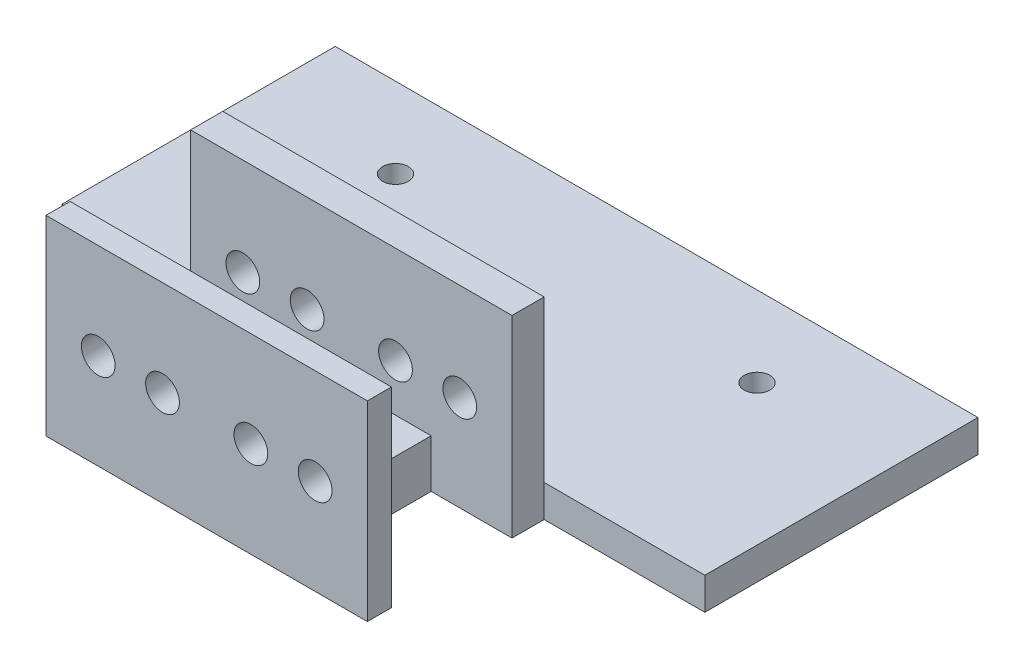
SolidWorks part; units mm, degrees
ref_plane "前视基准面" through (0, 0, 0) normal (0, 0, 1) x (1, 0, 0)
ref_plane "上视基准面" through (0, 0, 0) normal (0, 1, 0) x (1, 0, 0)
ref_plane "右视基准面" through (0, 0, 0) normal (1, 0, 0) x (0, 0, -1)
other "Configuration Table"
sketch "草图1" plane through (0, 0, 0) normal (0, 1, 0) x (1, 0, 0)
  line L1 (-40, 17) -> (40, 17)
  line L2 (-40, 17) -> (-40, -17)
  line L3 (-40, -17) -> (40, -17)
  line L4 (40, 17) -> (40, -17)
  line L5 (-40, 17) -> (40, -17) construction
  line L6 (-40, -17) -> (40, 17) construction
  point P0 (0, 0)
  dimension "D1" = 80
  dimension "D2" = 34
extrude "凸台-拉伸1" add sketch "草图1" along normal blind 4
sketch "草图2" plane through (0, 4, 0) normal (0, 1, 0) x (1, 0, 0)
  line L0 (-40, 7) -> (40, 7) construction
  line L1 (-40, 17) -> (-40, -17) construction
  line L2 (40, -17) -> (40, 17) construction
  line L4 (40, 17) -> (-40, 17) construction
  circle A0 centre (-22.5, 7) radius 1.6
  circle A1 centre (22.5, 7) radius 1.6
  point P8 (0, 7)
  point P9 (22.5, 7)
  point P10 (-22.5, 7)
  dimension "D1" = 10
  dimension "D2" = 22.5
  dimension "D3" = 22.5
extrude "切除-拉伸1" cut sketch "草图2" against normal up to next
sketch "草图3" plane through (0, 0, 17) normal (0, 0, 1) x (1, 0, 0)
  line L0 (-40, 0) -> (40, 0) construction
  line L1 (-20, 0) -> (20, 0)
  line L2 (-20, 0) -> (-20, 24)
  line L3 (20, 0) -> (20, 24)
  line L4 (-20, 24) -> (20, 24)
  point P0 (-20, 0)
  point P1 (20, 0)
  dimension "D1" = 20
  dimension "D2" = 20
extrude "凸台-拉伸2" add sketch "草图3" along normal blind 4
sketch "草图4" plane through (0, 0, 21) normal (0, 0, 1) x (1, 0, 0)
  line L0 (-20, 12) -> (20, 12) construction
  line L1 (-20, 24) -> (-20, 0) construction
  line L2 (20, 0) -> (20, 24) construction
  line L3 (-20, 3) -> (19.876, 3) construction
  line L4 (-20, 0) -> (20, 0) construction
  line L5 (-10.062, 6) -> (9.938, 6)
  line L6 (-10.062, 6) -> (-10.062, 0)
  line L7 (-10.062, 0) -> (9.938, 0)
  line L8 (9.938, 6) -> (9.938, 0)
  line L9 (-10.062, 6) -> (9.938, 0) construction
  line L10 (-10.062, 0) -> (9.938, 6) construction
  point P8 (-0.062, 3)
  dimension "D1" = 9
  dimension "D2" = 20
extrude "凸台-拉伸3" add sketch "草图4" along normal blind 15
sketch "草图5" plane through (0, 0, 36) normal (0, 0, 1) x (1, 0, 0)
  line L0 (-20, 0) -> (20, 0)
  line L1 (-20, 0) -> (-20, 23.7906)
  line L2 (20, 0) -> (20, 23.7906)
  line L3 (-20, 23.7906) -> (20, 23.7906)
extrude "凸台-拉伸4" add sketch "草图5" along normal blind 3
sketch "草图6" plane through (0, 0, 39) normal (0, 0, 1) x (1, 0, 0)
  line L0 (-20, 11.8953) -> (20, 11.8953) construction
  line L1 (-20, 23.7906) -> (-20, 0) construction
  line L2 (20, 0) -> (20, 23.7906) construction
  circle A0 centre (-13.5, 11.8953) radius 2.1
  circle A1 centre (-5.5, 11.8953) radius 2.1
  circle A2 centre (5.5, 11.8953) radius 2.1
  circle A3 centre (13.5, 11.8953) radius 2.1
  point P6 (-13.5, 11.8953)
  point P7 (-5.5, 11.8953)
  point P8 (5.5, 11.8953)
  point P9 (13.5, 11.8953)
  point P10 (0, 11.8953)
  dimension "D1" = 5.5
  dimension "D2" = 5.5
  dimension "D3" = 8
  dimension "D4" = 8
extrude "切除-拉伸2" cut sketch "草图6" against normal up to surface (22 mm away) up to face at (0, 14, 17)
sketch "草图8" plane through (0, 0, 17) normal (0, 0, -1) x (-1, 0, 0)
  line L0 (0, 0) -> (0, -12.5)
  line L1 (-40, 0) -> (40, 0) construction
  line L2 (0, -12.5) -> (27, -12.5)
  line L3 (0, -12.5) -> (-27, -12.5)
  dimension "D1" = 12.5
  dimension "D2" = 27
  dimension "D3" = 27
ref_plane "基准面1" through (0, -12.5, 0) normal (0, -1, 0) x (-1, 0, 0)
sketch "草图9" plane through (0, -12.5, 0) normal (0, -1, 0) x (-1, 0, 0)
  line L0 (27, -17) -> (27, -26.6611) construction
  line L1 (-27, -17) -> (-27, -21.8305) construction
